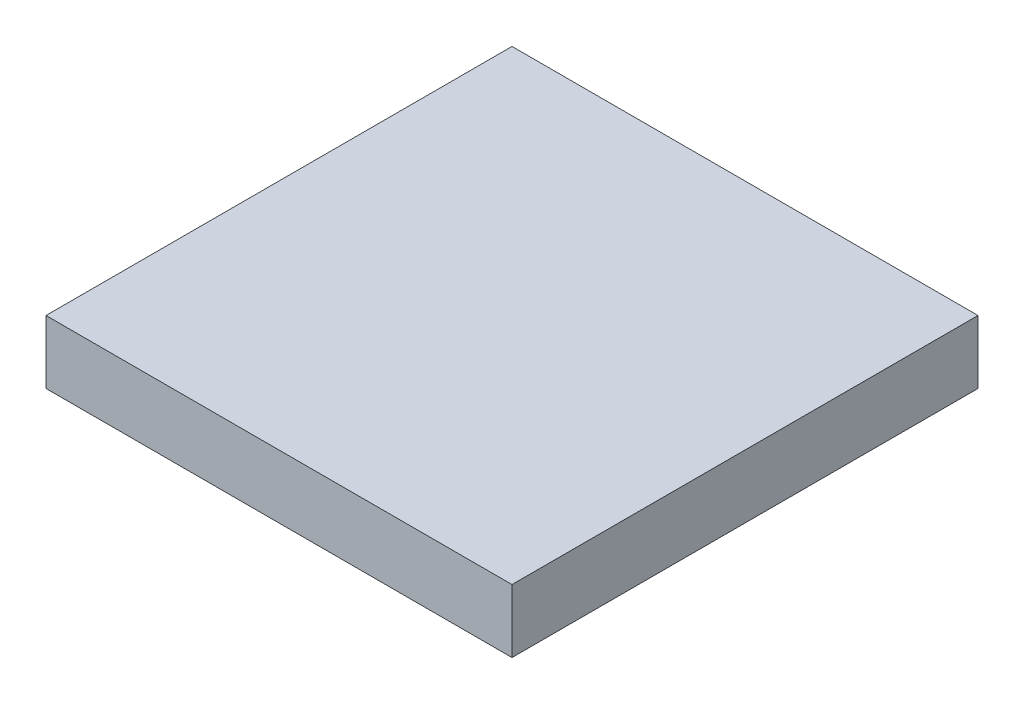
SolidWorks part; units mm, degrees
ref_plane "Front" through (0, 0, 0) normal (0, 0, 1) x (1, 0, 0)
ref_plane "Top" through (0, 0, 0) normal (0, 1, 0) x (1, 0, 0)
ref_plane "Right" through (0, 0, 0) normal (1, 0, 0) x (0, 0, -1)
sketch "草图1" plane through (0, 0, 0) normal (0, 1, 0) x (1, 0, 0)
  line L1 (-7, 7) -> (7, 7)
  line L2 (-7, 7) -> (-7, -7)
  line L3 (-7, -7) -> (7, -7)
  line L4 (7, 7) -> (7, -7)
  line L5 (-7, 7) -> (7, -7) construction
  line L6 (-7, -7) -> (7, 7) construction
  point P0 (0, 0)
  dimension "D1" = 14
extrude "凸台-拉伸1" add sketch "草图1" along normal blind 1.9
